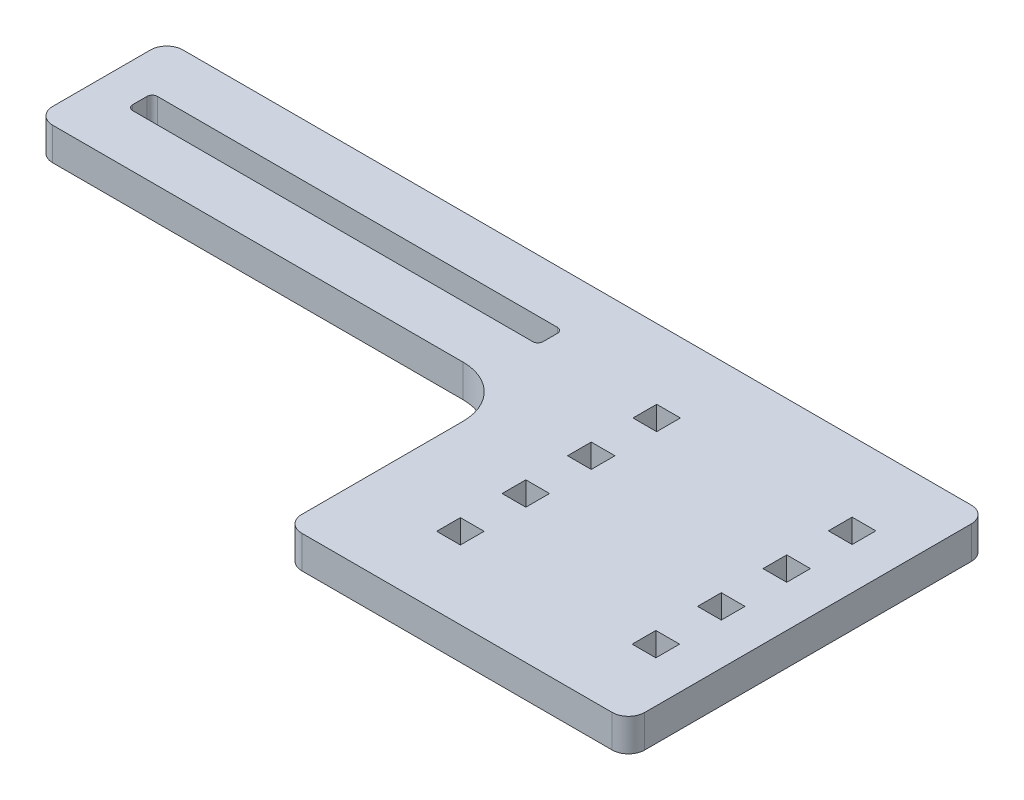
SolidWorks part; units mm, degrees
ref_plane "Front Plane" through (0, 0, 0) normal (0, 0, 1) x (1, 0, 0)
ref_plane "Top Plane" through (0, 0, 0) normal (0, 1, 0) x (1, 0, 0)
ref_plane "Right Plane" through (0, 0, 0) normal (1, 0, 0) x (0, 0, -1)
sketch "Sketch1" plane through (0, 0, 0) normal (0, 1, 0) x (1, 0, 0)
  line L0 (0, 0) -> (160, 0)
  line L1 (160, 0) -> (160, -70)
  line L2 (160, -70) -> (93.1472, -70)
  line L3 (93.1472, -70) -> (93.1472, -25.4)
  line L4 (93.1472, -25.4) -> (0, -25.4)
  line L5 (0, -25.4) -> (0, 0)
  line L6 (7.5, -10.3302) -> (87.5, -10.3302)
  line L11 (7.5, -10.3302) -> (7.5, -15.15)
  line L12 (7.5, -15.15) -> (87.5, -15.15)
  line L13 (87.5, -10.3302) -> (87.5, -15.15)
  line L58 (147.2472, -13.6493) -> (151.87, -13.6493)
  line L59 (151.87, -13.6493) -> (151.87, -18.2721)
  line L60 (147.2472, -18.2721) -> (151.87, -18.2721)
  line L61 (147.2472, -13.6493) -> (147.2472, -18.2721)
  line L66 (147.2472, -26.4021) -> (151.87, -26.4021)
  line L67 (151.87, -26.4021) -> (151.87, -31.0249)
  line L68 (147.2472, -31.0249) -> (151.87, -31.0249)
  line L69 (147.2472, -26.4021) -> (147.2472, -31.0249)
  line L74 (147.2472, -39.1549) -> (151.87, -39.1549)
  line L75 (151.87, -39.1549) -> (151.87, -43.7777)
  line L76 (147.2472, -43.7777) -> (151.87, -43.7777)
  line L77 (147.2472, -39.1549) -> (147.2472, -43.7777)
  line L86 (109.1472, -13.6493) -> (113.77, -13.6493)
  line L87 (113.77, -13.6493) -> (113.77, -18.2721)
  line L88 (109.1472, -18.2721) -> (113.77, -18.2721)
  line L89 (109.1472, -13.6493) -> (109.1472, -18.2721)
  line L90 (109.1472, -26.4021) -> (113.77, -26.4021)
  line L91 (113.77, -26.4021) -> (113.77, -31.0249)
  line L92 (109.1472, -31.0249) -> (113.77, -31.0249)
  line L93 (109.1472, -26.4021) -> (109.1472, -31.0249)
  line L94 (109.1472, -39.1549) -> (113.77, -39.1549)
  line L95 (113.77, -39.1549) -> (113.77, -43.7777)
  line L96 (109.1472, -43.7777) -> (113.77, -43.7777)
  line L97 (109.1472, -39.1549) -> (109.1472, -43.7777)
  line L99 (151.87, -51.9077) -> (147.2472, -51.9077)
  line L100 (151.87, -51.9077) -> (151.87, -56.5305)
  line L101 (151.87, -56.5305) -> (147.2472, -56.5305)
  line L102 (147.2472, -51.9077) -> (147.2472, -56.5305)
  line L103 (113.77, -56.5305) -> (109.1472, -56.5305)
  line L104 (113.77, -56.5305) -> (113.77, -51.9077)
  line L105 (113.77, -51.9077) -> (109.1472, -51.9077)
  line L106 (109.1472, -56.5305) -> (109.1472, -51.9077)
  dimension "D2" = 25.4
  dimension "D3" = 16
  dimension "D4" = 70
  dimension "D5" = 10.25
  dimension "D6" = 7.5
  dimension "D11" = 4.6228
  dimension "D12" = 8.13
  dimension "D13" = 8.13
  dimension "D14" = 33.4772
  dimension "D15" = 8.13
  dimension "D16" = 160
  dimension "D17" = 8.13
  dimension "D10" = 80
extrude "Boss-Extrude1" add sketch "Sketch1" along normal blind 6.35
fillet "Fillet2" radius 3.175 1 edges at (0, 3.175, 25.4)
fillet "Fillet3" radius 3.175 4 edges at (93.1472, 3.175, 70) (160, 3.175, 70) (160, 3.175, 0) (0, 3.175, 0)
fillet "Fillet4" radius 10 1 edges at (93.1472, 3.175, 25.4)
fillet "Fillet5" radius 1 4 edges at (87.5, 3.175, 15.15) (87.5, 3.175, 10.3302) (7.5, 3.175, 10.3302) (7.5, 3.175, 15.15)
